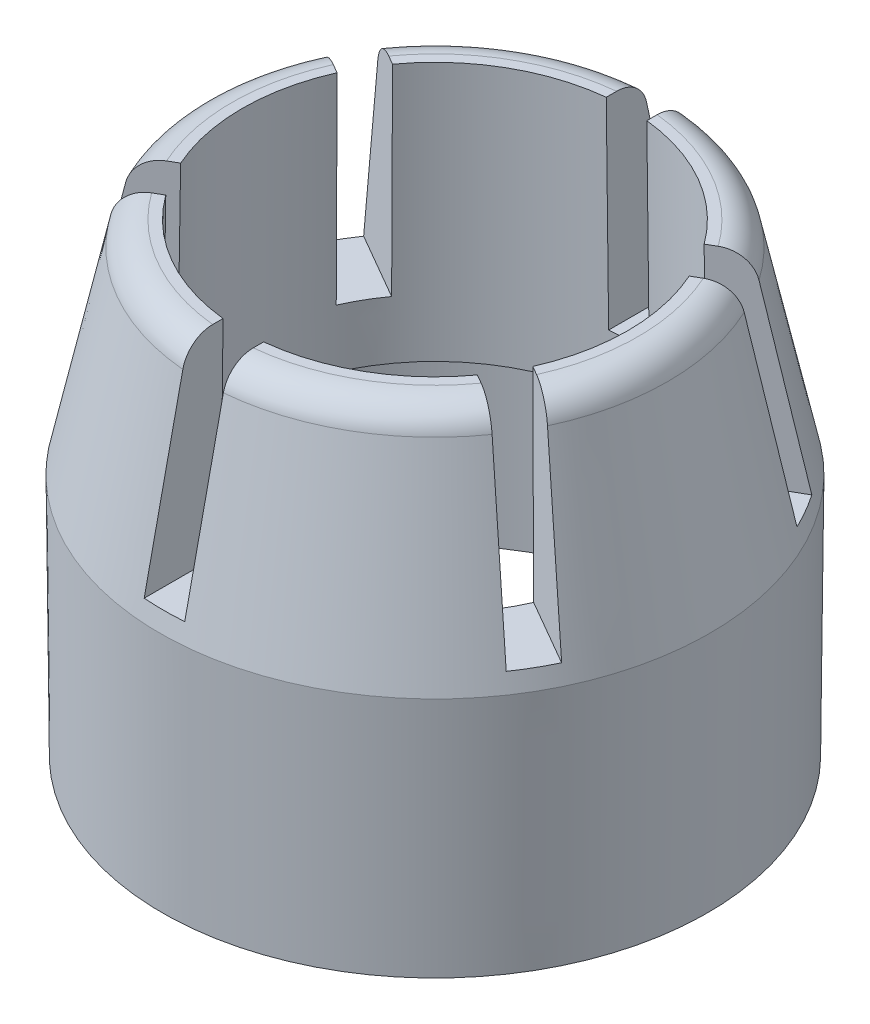
SolidWorks part; units mm, degrees
ref_plane "Front Plane" through (0, 0, 0) normal (0, 0, 1) x (1, 0, 0)
ref_plane "Top Plane" through (0, 0, 0) normal (0, 1, 0) x (1, 0, 0)
ref_plane "Right Plane" through (0, 0, 0) normal (1, 0, 0) x (0, 0, -1)
sketch "Sketch1" plane through (0, 0, 0) normal (0, 0, 1) x (1, 0, 0)
  line L0 (0, 0) -> (0, 10.854) construction
  line L1 (12.7, -3.2534) -> (13.4471, -3.2534) construction
  line L2 (12.7, -3.2534) -> (13.4471, -3.2534)
  line L8 (12.7, 6.7466) -> (12.7, -3.2534)
  line L11 (13.4471, -3.2534) -> (13.5633, 8.7466)
  line L13 (9.5, 19.6266) -> (10.0075, 19.6266)
  line L14 (11.4738, 18.4426) -> (13.5633, 8.7466)
  line L15 (9.5, 19.6266) -> (9.65, 6.7466)
  line L16 (9.65, 6.7466) -> (12.7, 6.7466)
  arc A0 (11.4738, 18.4426) -> (10.0075, 19.6266) centre (10.0075, 18.1266) ccw
  dimension "D8" = 1.5
  dimension "D1" = 12.7
  dimension "D2" = 9.5
  dimension "D3" = 10
  dimension "D4" = 22.88
  dimension "D5" = 12
  dimension "D6" = 9.65
  dimension "D7" = 13.5633
revolve "Revolve1" add sketch "Sketch1" angle 360 about L0
sketch "Sketch3" plane through (0, 19.6266, 0) normal (0, 1, 0) x (1, 0, 0)
  line L0 (0, 0) -> (0, 13.8007) construction
  line L2 (-1, 4.6969) -> (1, 4.6969)
  line L3 (-1, 4.6969) -> (-1, 15.318)
  line L4 (-1, 15.318) -> (1, 15.318)
  line L5 (1, 4.6969) -> (1, 15.318)
  line L6 (-1, 4.6969) -> (1, 15.318) construction
  line L7 (-1, 15.318) -> (1, 4.6969) construction
  circle A0 centre (0, 0) radius 10.0075 construction
  point P3 (0, 10.0075)
  dimension "D1" = 2
extrude "Cut-Extrude1" cut sketch "Sketch3" against normal blind 10
pattern_circular "CirPattern1" count 6 every 60 about axis through (0, 0, 0) along (0, 1, 0) of "Cut-Extrude1"
